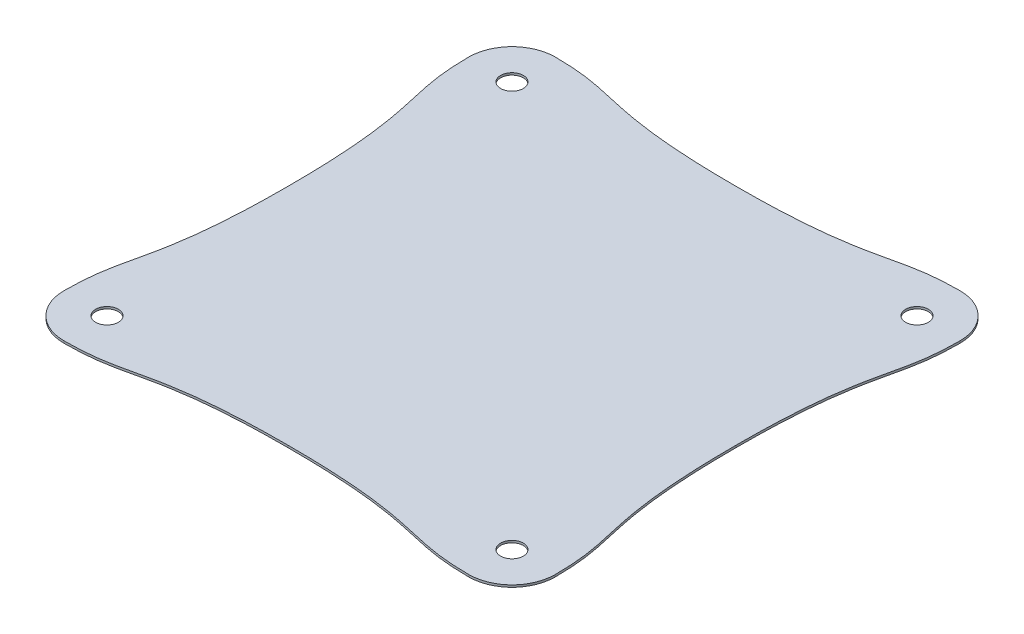
SolidWorks part; units mm, degrees
ref_plane "Front Plane" through (0, 0, 0) normal (0, 0, 1) x (1, 0, 0)
ref_plane "Top Plane" through (0, 0, 0) normal (0, 1, 0) x (1, 0, 0)
ref_plane "Right Plane" through (0, 0, 0) normal (1, 0, 0) x (0, 0, -1)
sketch "Sketch1" plane through (0, 0, 0) normal (0, 1, 0) x (1, 0, 0)
  line L0 (0, 75) -> (75, 0) construction
  line L1 (0, 0) -> (75, 0) construction
  line L2 (0, 0) -> (0, 75) construction
  line L3 (0, 75) -> (75, 75) construction
  line L4 (75, 0) -> (75, 75) construction
  line L5 (0, 75) -> (0, 93.0382) construction
  line L6 (0, 75) -> (-26.3477, 75) construction
  line L7 (75, 75) -> (75, 94.5096) construction
  line L8 (75, 75) -> (107.0147, 75) construction
  line L9 (37.5, 75) -> (37.5, 96.1148) construction
  line L10 (0, 79) -> (75, 79) construction
  line L11 (75, 83) -> (62.5, 83) construction
  line L12 (0, 83) -> (12.5, 83) construction
  line L13 (12.5, 83) -> (12.5, 79) construction
  line L14 (12.5, 79) -> (37.5, 79) construction
  line L15 (62.5, 83) -> (62.5, 79) construction
  line L16 (62.5, 79) -> (37.5, 79) construction
  line L17 (83, 0) -> (83, 12.5) construction
  line L18 (83, 75) -> (83, 62.5) construction
  line L19 (83, 62.5) -> (79, 62.5) construction
  line L20 (79, 62.5) -> (79, 37.5) construction
  line L21 (83, 12.5) -> (79, 12.5) construction
  line L22 (79, 12.5) -> (79, 37.5) construction
  line L23 (0, -8) -> (12.5, -8) construction
  line L24 (75, -8) -> (62.5, -8) construction
  line L25 (62.5, -8) -> (62.5, -4) construction
  line L26 (62.5, -4) -> (37.5, -4) construction
  line L27 (12.5, -8) -> (12.5, -4) construction
  line L28 (12.5, -4) -> (37.5, -4) construction
  line L29 (-8, 75) -> (-8, 62.5) construction
  line L30 (-8, 0) -> (-8, 12.5) construction
  line L31 (-8, 12.5) -> (-4, 12.5) construction
  line L32 (-4, 12.5) -> (-4, 37.5) construction
  line L33 (-8, 62.5) -> (-4, 62.5) construction
  line L34 (-4, 62.5) -> (-4, 37.5) construction
  circle A0 centre (0, 75) radius 2.1
  circle A1 centre (75, 75) radius 2.1
  circle A2 centre (75, 0) radius 2.1
  circle A3 centre (0, 0) radius 2.1
  arc A4 (0, 83) -> (-8, 75) centre (0, 75) ccw
  arc A5 (83, 75) -> (75, 83) centre (75, 75) ccw
  arc A6 (83, 75) -> (75, 83) centre (75, 75) ccw
  arc A7 (75, -8) -> (83, 0) centre (75, 0) ccw
  arc A8 (75, -8) -> (83, 0) centre (75, 0) ccw
  arc A9 (-8, 0) -> (0, -8) centre (0, 0) ccw
  arc A10 (-8, 0) -> (0, -8) centre (0, 0) ccw
  arc A11 (0, 83) -> (-8, 75) centre (0, 75) ccw
  spline S0 degree 3 poles (0, 83) (12.5, 83) (12.5, 79) (37.5, 79) knots 0 0 0 0 1 1 1 1
  spline S1 degree 3 poles (75, 83) (62.5, 83) (62.5, 79) (37.5, 79) knots 0 0 0 0 1 1 1 1
  spline S2 degree 3 poles (83, 75) (83, 62.5) (79, 62.5) (79, 37.5) knots 0 0 0 0 1 1 1 1
  spline S3 degree 3 poles (83, 0) (83, 12.5) (79, 12.5) (79, 37.5) knots 0 0 0 0 1 1 1 1
  spline S4 degree 3 poles (75, -8) (62.5, -8) (62.5, -4) (37.5, -4) knots 0 0 0 0 1 1 1 1
  spline S5 degree 3 poles (0, -8) (12.5, -8) (12.5, -4) (37.5, -4) knots 0 0 0 0 1 1 1 1
  spline S6 degree 3 poles (-8, 0) (-8, 12.5) (-4, 12.5) (-4, 37.5) knots 0 0 0 0 1 1 1 1
  spline S7 degree 3 poles (-8, 75) (-8, 62.5) (-4, 62.5) (-4, 37.5) knots 0 0 0 0 1 1 1 1
  point P25 (37.5, 37.5)
  point P63 (37.5, 37.5)
  dimension "D2" = 4.2
  dimension "D3" = 8
  dimension "D4" = 4
  dimension "D1" = 75
  dimension "D5" = 25
  dimension "D7" = 4
extrude "Boss-Extrude1" add sketch "Sketch1" along normal blind 0.4 contours A4 S7 S6 A9 S5 S4 A7 S3 S2 A5 S1 S0 A0 A1 A2 A3
